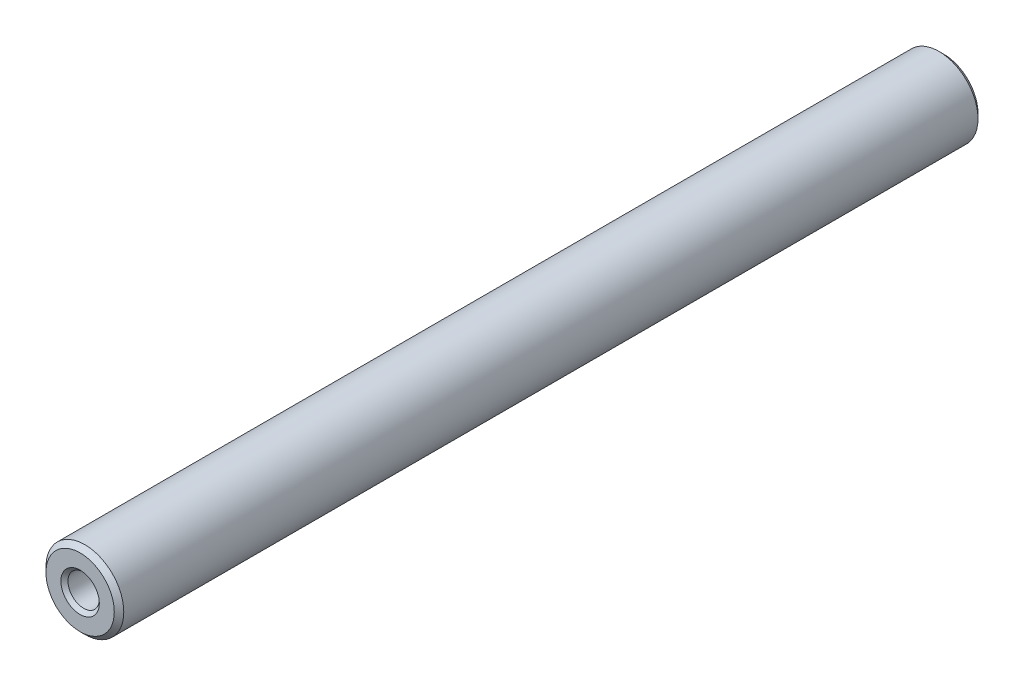
SolidWorks part; units mm, degrees
ref_plane "Front Plane" through (0, 0, 0) normal (0, 0, 1) x (1, 0, 0)
ref_plane "Top Plane" through (0, 0, 0) normal (0, 1, 0) x (1, 0, 0)
ref_plane "Right Plane" through (0, 0, 0) normal (1, 0, 0) x (0, 0, -1)
sketch "Sketch1" plane through (0, 0, 0) normal (0, 0, 1) x (1, 0, 0)
  circle A0 centre (0, 0) radius 4.1
  dimension "D1" = 8.2
extrude "Blank" add sketch "Sketch1" against normal blind 91
hole_wizard "Furo 1 -  M4x11.5" positions "Sketch2" profile "Sketch3" tap size "M4x0.7" standard "ANSI Metric"
sketch "Sketch2" plane through (0, 0, 0) normal (0, 0, 1) x (1, 0, 0)
  point P0 (0, 0)
sketch "Sketch3" plane through (0, 0, 0) normal (1, 0, 0) x (0, -1, 0)
  line L0 (0, 0) -> (0, 11.5)
  line L1 (0, 11.5) -> (1.65, 10.5086)
  line L2 (1.65, 10.5086) -> (1.65, 0.375)
  line L3 (1.65, 0.375) -> (2.025, 0)
  line L5 (2.025, 0) -> (0, 0)
  line L6 (-1.65, 0.375) -> (-2.025, 0) construction
  line L10 (0, 11.5) -> (-1.65, 10.5086) construction
  line L11 (0, -6.35) -> (0, 107.95) construction
  dimension "Tap Drill Dia." = 3.3
  dimension "Tap Drill Depth" = 11.5
  dimension "Near C'Sink Dia." = 4.05
  dimension "Near C'Sink Angle" = 90
  dimension "Drill Angle" = 118
cosmetic thread "Hole Thread1"
hole_wizard "Furo 2 -  M4x11.5" positions "Sketch4" profile "Sketch5" tap size "M4x0.7" standard "ANSI Metric"
sketch "Sketch4" plane through (0, 0, -91) normal (0, 0, -1) x (-1, 0, 0)
  point P0 (0, 0)
sketch "Sketch5" plane through (0, 0, -91) normal (1, 0, 0) x (0, 1, 0)
  line L0 (0, 0) -> (0, 11.5)
  line L1 (0, 11.5) -> (1.65, 10.5086)
  line L2 (1.65, 10.5086) -> (1.65, 0.375)
  line L3 (1.65, 0.375) -> (2.025, 0)
  line L5 (2.025, 0) -> (0, 0)
  line L6 (-1.65, 0.375) -> (-2.025, 0) construction
  line L10 (0, 11.5) -> (-1.65, 10.5086) construction
  line L11 (0, -6.35) -> (0, 107.95) construction
  dimension "Tap Drill Dia." = 3.3
  dimension "Tap Drill Depth" = 11.5
  dimension "Near C'Sink Dia." = 4.05
  dimension "Near C'Sink Angle" = 90
  dimension "Drill Angle" = 118
cosmetic thread "Hole Thread2"
chamfer "Chanfros" distance 0.5 angle 45 2 edges at (4.1, 0, -91) (4.1, 0, 0)
